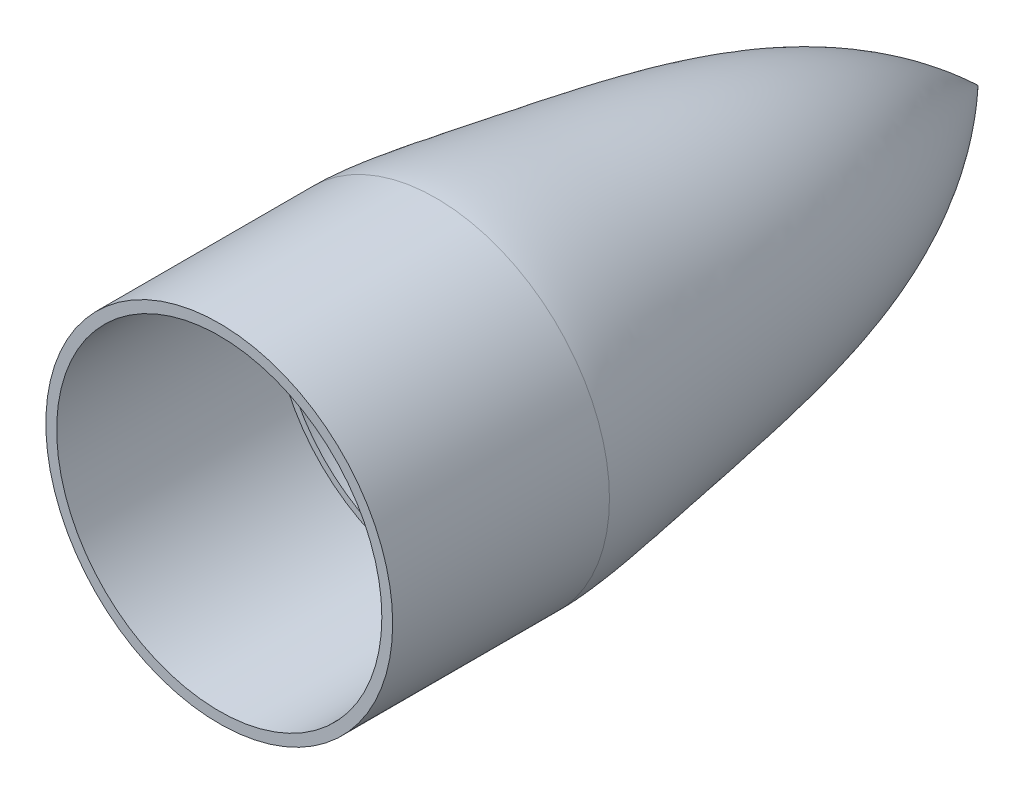
SolidWorks part; units mm, degrees
material "ABS"
ref_plane "前视基准面" through (0, 0, 0) normal (0, 0, 1) x (1, 0, 0)
ref_plane "上视基准面" through (0, 0, 0) normal (0, 1, 0) x (1, 0, 0)
ref_plane "右视基准面" through (0, 0, 0) normal (1, 0, 0) x (0, 0, -1)
sketch "草图1" plane through (0, 0, 0) normal (0, 1, 0) x (1, 0, 0)
  line L0 (0, 21.2081) -> (0, 26.5653) construction
  line L1 (0, 0) -> (15, 0) construction
  line L2 (15, 0) -> (15, 20)
  line L3 (15, 20) -> (16, 20)
  line L4 (16, 20) -> (16, 0)
  line L5 (16, 0) -> (15, 0)
  line L6 (15, 20) -> (14.4, 20)
  line L7 (14.4, 20) -> (14.4, 16.9033) construction
  line L8 (0, 70) -> (0, 68.4)
  spline S0 degree 3 poles (16, 20) (16, 23.0077) (12.4425, 43.7503) (10.3576, 59.0893) (0, 70) knots 0 0 0 0 0.236447 1 1 1 1
  spline S1 degree 3 poles (14.4, 20) (14.4, 22.1569) (10.8898, 43.0378) (10.6208, 57.3163) (0, 68.4) knots 0 0 0 0 0.204356 1 1 1 1
  point P10 (9.443, 57.555)
  point P17 (7.7072, 56.8607)
  point P19 (14.4, 32.5147)
  point P20 (8.5367, 57.09)
  dimension "D1" = 1
  dimension "D2" = 15
  dimension "D3" = 20
  dimension "D4" = 0.6
  dimension "D5" = 1.6
  dimension "D6" = 70
revolve "旋转1" add sketch "草图1" angle 360 about L0
